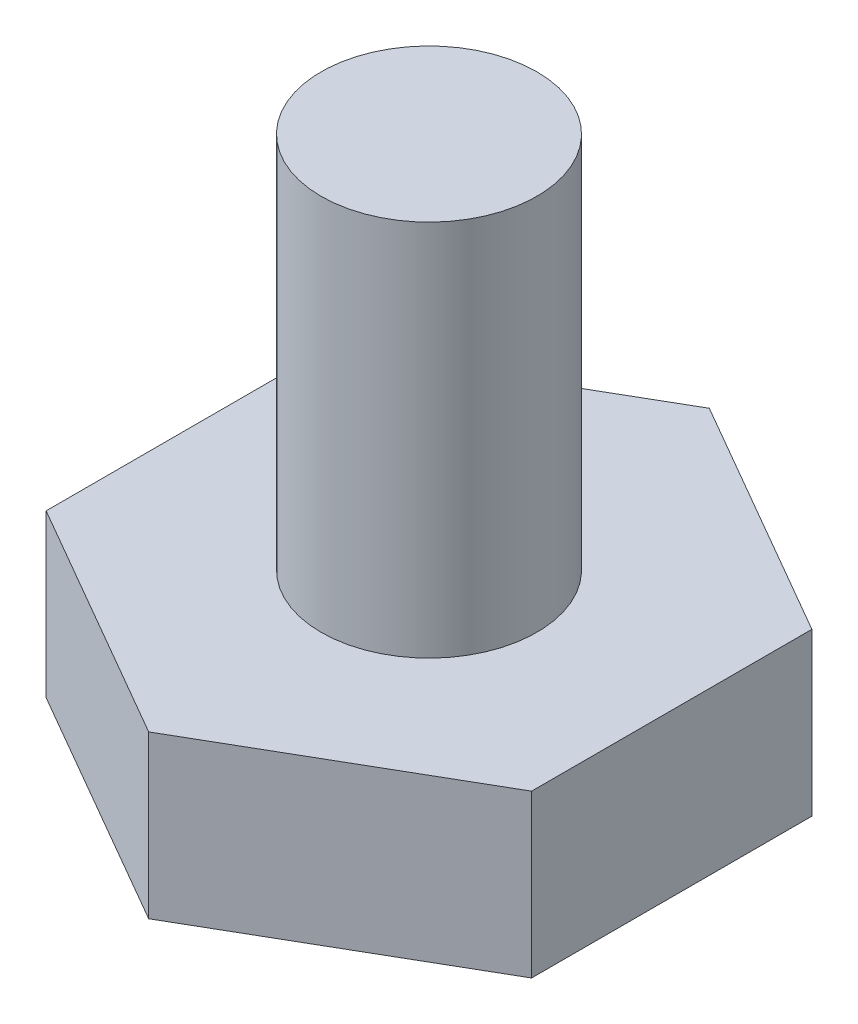
SolidWorks part; units mm, degrees
ref_plane "Front Plane" through (0, 0, 0) normal (0, 0, 1) x (1, 0, 0)
ref_plane "Top Plane" through (0, 0, 0) normal (0, 1, 0) x (1, 0, 0)
ref_plane "Right Plane" through (0, 0, 0) normal (1, 0, 0) x (0, 0, -1)
sketch "Sketch1" plane through (0, 0, 0) normal (0, 1, 0) x (1, 0, 0)
  line L1 (0, 8.2489) -> (-7.1438, 4.1244)
  line L2 (-7.1438, 4.1244) -> (-7.1437, -4.1244)
  line L3 (-7.1437, -4.1244) -> (0, -8.2489)
  line L4 (0, -8.2489) -> (7.1438, -4.1244)
  line L5 (7.1438, -4.1244) -> (7.1437, 4.1244)
  line L6 (7.1437, 4.1244) -> (0, 8.2489)
  circle A0 centre (0, 0) radius 7.1437 construction
  dimension "D1" = 14.2875
extrude "Boss-Extrude1" add sketch "Sketch1" along normal mid plane 4.7625
sketch "Sketch2" plane through (0, 2.3813, 0) normal (0, 1, 0) x (1, 0, 0)
  circle A0 centre (0, 0) radius 3.175
  dimension "D1" = 6.35
extrude "Boss-Extrude2" add sketch "Sketch2" along normal blind 11.1125
